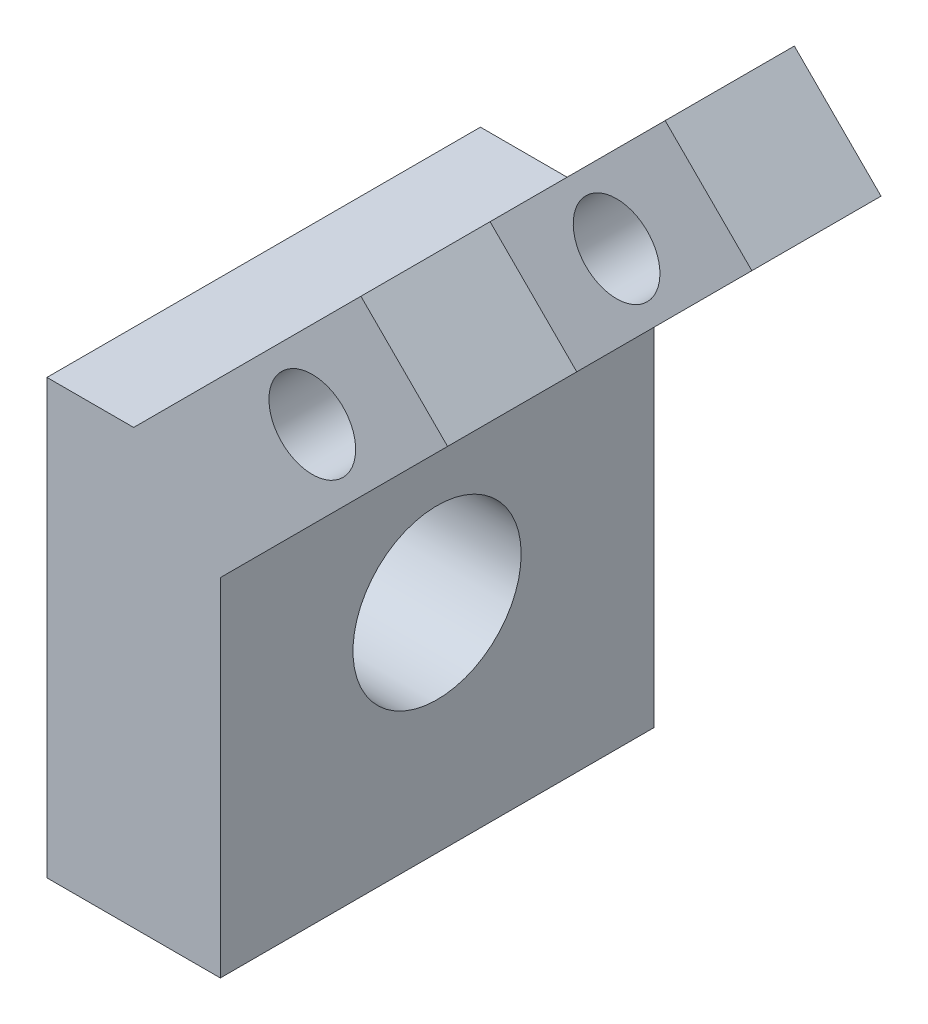
SolidWorks part; units mm, degrees
ref_plane "Front Plane" through (0, 0, 0) normal (0, 0, 1) x (1, 0, 0)
ref_plane "Top Plane" through (0, 0, 0) normal (0, 1, 0) x (1, 0, 0)
ref_plane "Right Plane" through (0, 0, 0) normal (1, 0, 0) x (0, 0, -1)
sketch "Sketch1" plane through (0, 0, 0) normal (1, 0, 0) x (0, 0, -1)
  line L1 (-12.5, 12.5) -> (12.5, 12.5)
  line L2 (-12.5, 12.5) -> (-12.5, -12.5)
  line L3 (-12.5, -12.5) -> (12.5, -12.5)
  line L4 (12.5, 12.5) -> (12.5, -12.5)
  line L5 (-12.5, 12.5) -> (12.5, -12.5) construction
  line L6 (-12.5, -12.5) -> (12.5, 12.5) construction
  circle A0 centre (0, 0) radius 4.85
  dimension "D1" = 9.7
  dimension "D2" = 25
extrude "Boss-Extrude1" add sketch "Sketch1" along normal blind 10
sketch "Sketch2" plane through (0, 0, 0) normal (0, 0, 1) x (1, 0, 0)
  line L0 (10, 12.5) -> (17.7964, 12.5) construction
  line L1 (10, 12.5) -> (16.0379, 18.5379) construction
  line L2 (5, 12.5) -> (18.1066, 25.6066)
  line L3 (10, 12.5) -> (0, 12.5) construction
  line L4 (18.1066, 25.6066) -> (23.1066, 20.6066)
  line L5 (23.1066, 20.6066) -> (10, 7.5)
  line L6 (10, 12.5) -> (10, -12.5) construction
  line L7 (5, 12.5) -> (10, 12.5)
  line L8 (10, 12.5) -> (10, 7.5)
  point P12 (20.6066, 23.1066)
  dimension "D1" = 45
  dimension "D2" = 15
extrude "Boss-Extrude2" add sketch "Sketch2" along normal mid plane 25
sketch "Sketch3" plane through (0, 0, 0) normal (0, 0, 1) x (1, 0, 0)
  line L0 (23.1066, 20.6066) -> (18.1066, 25.6066) construction
  line L1 (10, 7.5) -> (23.1066, 20.6066) construction
  line L2 (18.1066, 25.6066) -> (5, 12.5) construction
  line L3 (23.1066, 20.6066) -> (18.1066, 25.6066)
  line L4 (10, 7.5) -> (23.1066, 20.6066)
  line L5 (18.1066, 25.6066) -> (5, 12.5)
  line L6 (5, 12.5) -> (10, 12.5)
  line L7 (10, 7.5) -> (10, 12.5)
extrude "Cut-Extrude1" cut sketch "Sketch3" against normal mid plane 10.1
sketch "Sketch4" plane through (0, 0, -12.5) normal (0, 0, -1) x (-1, 0, 0)
  line L0 (-10, 7.5) -> (-10, 12.5089) construction
  line L1 (-10, 12.5089) -> (-5, 12.5) construction
  line L2 (-21.3388, 18.8388) -> (-16.3388, 23.8388) construction
  line L3 (-10, 7.5) -> (-23.1066, 20.6066) construction
  line L4 (-18.1066, 25.6066) -> (-5, 12.5) construction
  line L5 (-14.2678, 11.7678) -> (-9.2678, 16.7678) construction
  line L6 (-23.1066, 20.6066) -> (-18.1066, 25.6066) construction
  line L7 (-18.8388, 21.3388) -> (-11.7678, 14.2678) construction
  circle A0 centre (-15.3033, 17.8033) radius 2.5
  point P13 (-18.8388, 21.3388)
  dimension "D4" = 5
  dimension "D1" = 10
  dimension "D2" = 2.5
  dimension "D3" = 2.4937
extrude "Cut-Extrude2" cut sketch "Sketch4" against normal through all
scale "Scale1" scale about centroid uniform scaling yes scale factor 1.5
